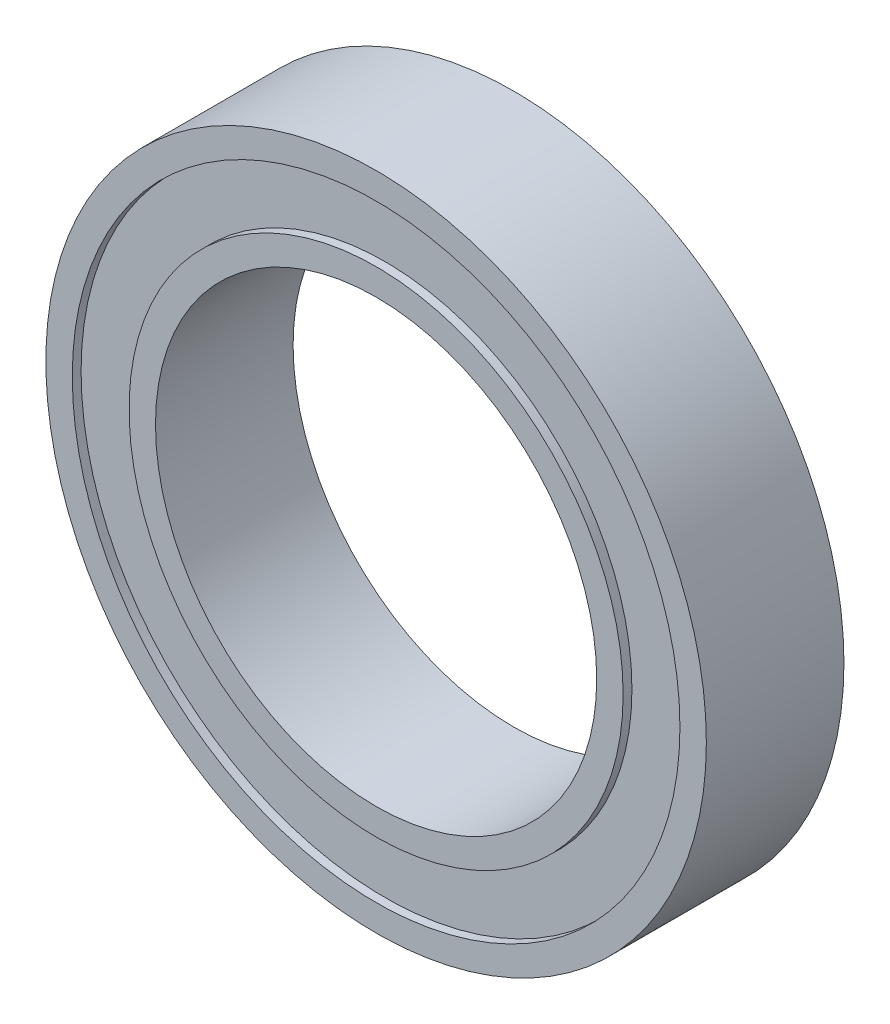
SolidWorks part; units mm, degrees
ref_plane "Front Plane" through (0, 0, 0) normal (0, 0, 1) x (1, 0, 0)
ref_plane "Top Plane" through (0, 0, 0) normal (0, 1, 0) x (1, 0, 0)
ref_plane "Right Plane" through (0, 0, 0) normal (1, 0, 0) x (0, 0, -1)
sketch "Sketch1" plane through (0, 0, 0) normal (0, 0, 1) x (1, 0, 0)
  circle A0 centre (0, 0) radius 9.525
  circle A1 centre (0, 0) radius 6.3627
  dimension "D1" = 12.7254
  dimension "D2" = 19.05
extrude "Boss-Extrude1" add sketch "Sketch1" along normal mid plane 3.9688
sketch "Sketch2" plane through (0, 0, 1.9844) normal (0, 0, 1) x (1, 0, 0)
  circle A0 centre (0, 0) radius 7.1247
  circle A1 centre (0, 0) radius 8.763
  circle A3 centre (0, 0) radius 9.525 construction
  circle A4 centre (0, 0) radius 6.3627 construction
  dimension "D1" = 0.762
  dimension "D2" = 0.762
extrude "Cut-Extrude1" cut sketch "Sketch2" against normal blind 0.254
mirror "Mirror1" about plane through (0, 0, 0) normal (0, 0, 1) of "Cut-Extrude1"
